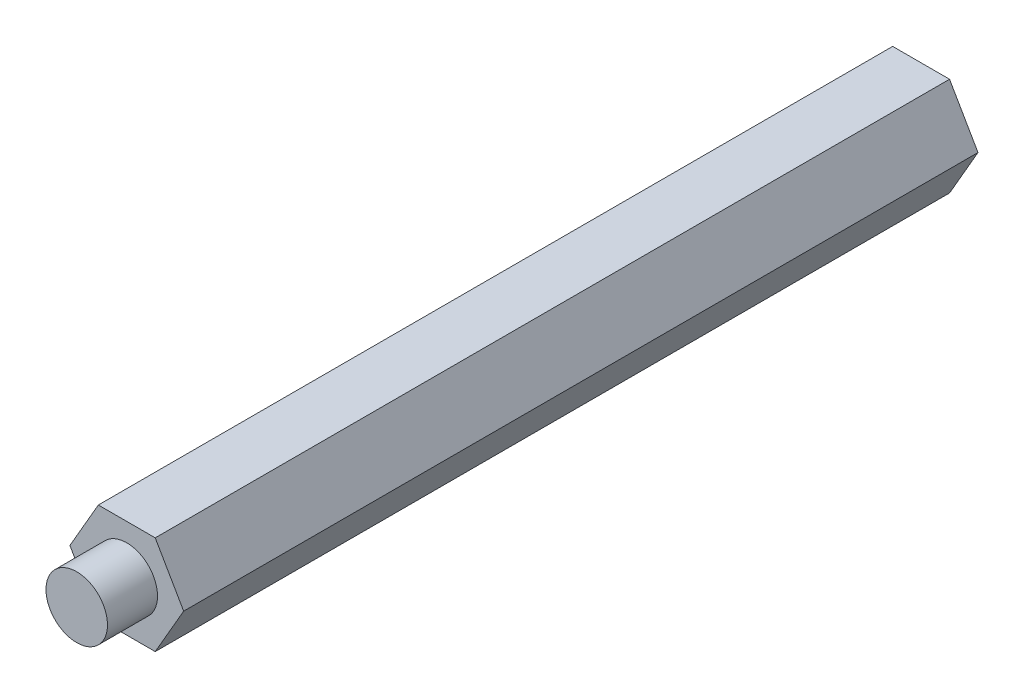
SolidWorks part; units mm, degrees
material "3003 Alloy"
ref_plane "Front Plane" through (0, 0, 0) normal (0, 0, 1) x (1, 0, 0)
ref_plane "Top Plane" through (0, 0, 0) normal (0, 1, 0) x (1, 0, 0)
ref_plane "Right Plane" through (0, 0, 0) normal (1, 0, 0) x (0, 0, -1)
sketch "Sketch1" plane through (0, 0, 0) normal (0, 0, 1) x (1, 0, 0)
  line L1 (3.6084, 0) -> (1.8042, 3.125)
  line L2 (1.8042, 3.125) -> (-1.8042, 3.125)
  line L3 (-1.8042, 3.125) -> (-3.6084, 0)
  line L4 (-3.6084, 0) -> (-1.8042, -3.125)
  line L5 (-1.8042, -3.125) -> (1.8042, -3.125)
  line L6 (1.8042, -3.125) -> (3.6084, 0)
  circle A0 centre (0, 0) radius 3.125 construction
  dimension "D1" = 6.25
extrude "Boss-Extrude1" add sketch "Sketch1" along normal up to surface (50.385 mm away)
sketch "Sketch2" plane through (0, 0, 0) normal (0, 0, 1) x (1, 0, 0)
  circle A0 centre (0, 0) radius 2.25
  dimension "D1" = 4.5
extrude "Cut-Extrude2" [suppressed] cut sketch "Sketch2" along normal offset from surface (0.2 mm away) 0.06
sketch "Sketch3" plane through (0, 0, 50.385) normal (0, 0, 1) x (1, 0, 0)
  circle A0 centre (0, 0) radius 1.95
  dimension "D1" = 3.9
extrude "Boss-Extrude2" add sketch "Sketch3" along normal up to surface (3.175 mm away)
equation "\"D1@Sketch1\"=6.35-0.1"
